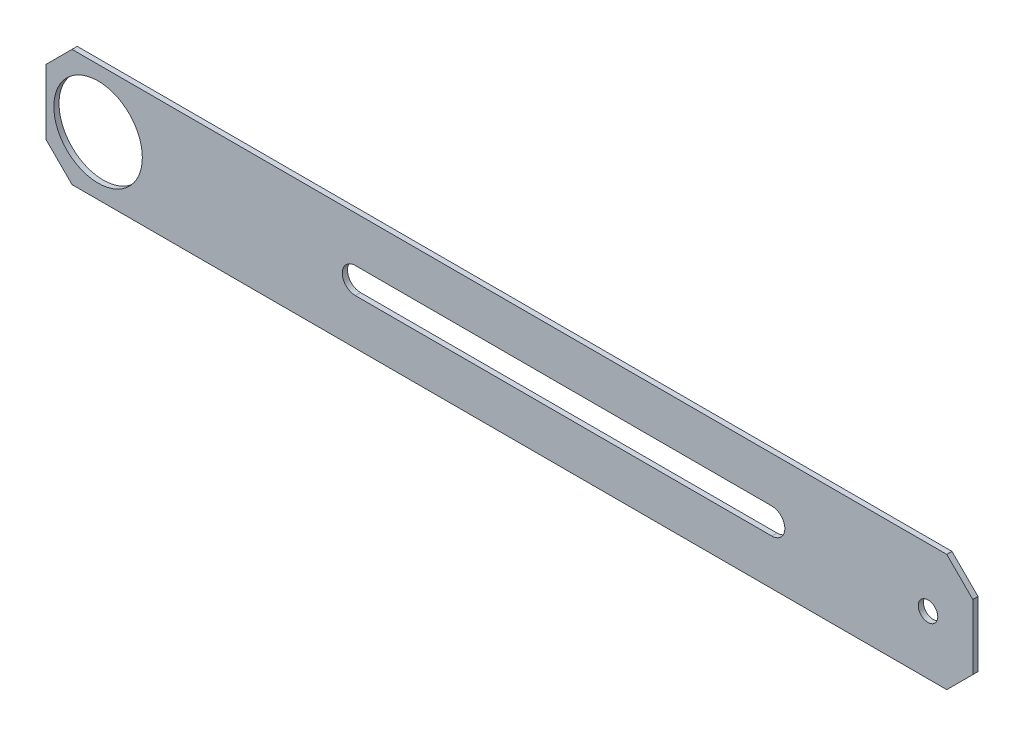
SolidWorks part; units mm, degrees
ref_plane "Front Plane" through (0, 0, 0) normal (0, 0, 1) x (1, 0, 0)
ref_plane "Top Plane" through (0, 0, 0) normal (0, 1, 0) x (1, 0, 0)
ref_plane "Right Plane" through (0, 0, 0) normal (1, 0, 0) x (0, 0, -1)
sketch "Sketch1" plane through (0, 0, 0) normal (0, 0, 1) x (1, 0, 0)
  line L0 (0, 57.15) -> (904.24, 57.15) construction
  line L1 (0, 0) -> (904.24, 0)
  line L2 (0, 0) -> (0, 114.3)
  line L3 (0, 114.3) -> (904.24, 114.3)
  line L4 (904.24, 0) -> (904.24, 114.3)
  line L5 (301.752, 57.15) -> (708.152, 57.15) construction
  line L6 (301.752, 69.85) -> (708.152, 69.85)
  line L7 (301.752, 44.45) -> (708.152, 44.45)
  circle A0 centre (50.8, 57.15) radius 43.18
  circle A1 centre (860.552, 57.15) radius 9.525
  arc A4 (301.752, 69.85) -> (301.752, 44.45) centre (301.752, 57.15) ccw
  arc A5 (708.152, 44.45) -> (708.152, 69.85) centre (708.152, 57.15) ccw
  point P13 (504.952, 57.15)
  dimension "D3" = 86.36
  dimension "D5" = 19.05
  dimension "D7" = 25.4
  dimension "D9" = 152.4
  dimension "D1" = 114.3
  dimension "D2" = 904.24
  dimension "D4" = 50.8
  dimension "D6" = 809.752
  dimension "D8" = 406.4
extrude "Boss-Extrude1" add sketch "Sketch1" along normal blind 5.08
chamfer "Chamfer1" distance 25.4 angle 45 4 edges at (904.24, 0, 2.54) (904.24, 114.3, 2.54) (0, 0, 2.54) (0, 114.3, 2.54)
